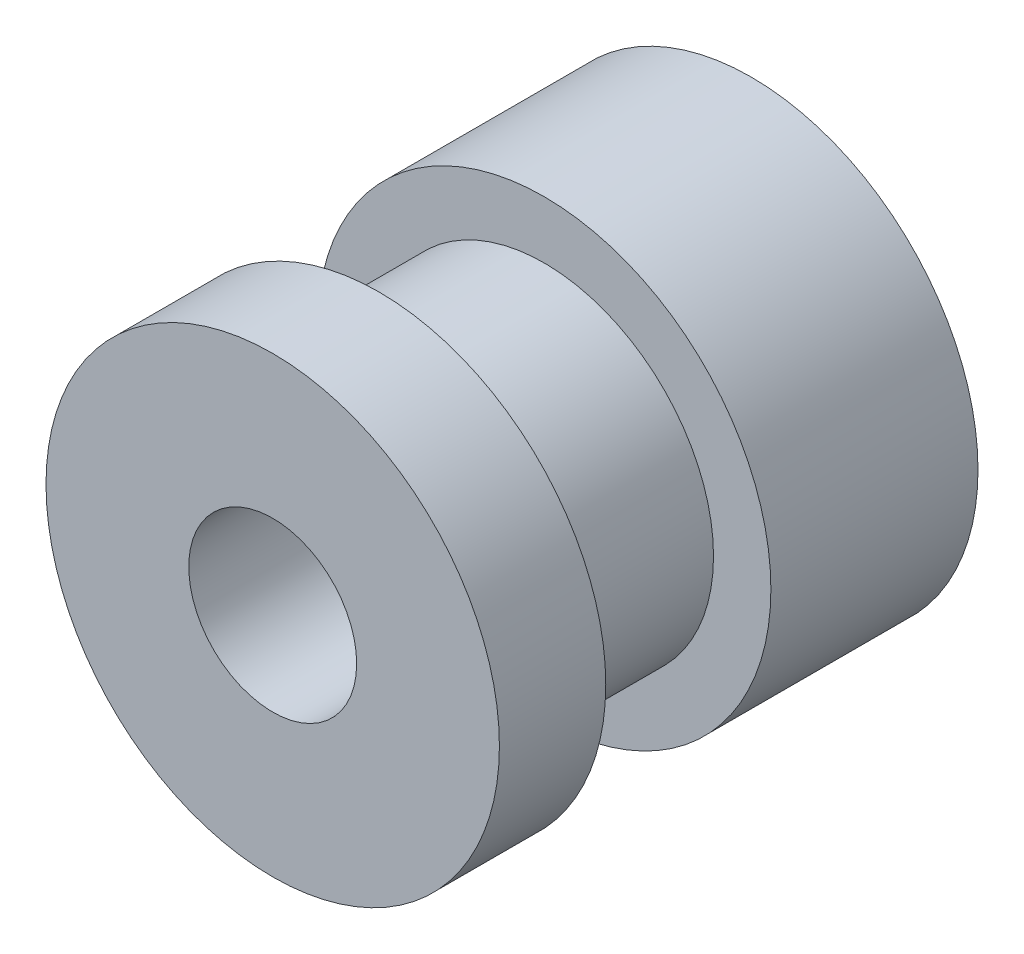
SolidWorks part; units mm, degrees
ref_plane "Front Plane" through (0, 0, 0) normal (0, 0, 1) x (1, 0, 0)
ref_plane "Top Plane" through (0, 0, 0) normal (0, 1, 0) x (1, 0, 0)
ref_plane "Right Plane" through (0, 0, 0) normal (1, 0, 0) x (0, 0, -1)
sketch "Sketch1" plane through (0, 0, 0) normal (0, 1, 0) x (1, 0, 0)
  line L0 (0, 0) -> (0, 15.8386) construction
  line L1 (-3, 0) -> (-8.1, 0)
  line L2 (-8.1, 0) -> (-8.1, 3.8)
  line L3 (-8.1, 3.8) -> (-6.05, 3.8)
  line L4 (-6.05, 3.8) -> (-6.05, 9.7)
  line L5 (-6.05, 9.7) -> (-8.1, 9.7)
  line L6 (-8.1, 9.7) -> (-8.1, 17.1)
  line L7 (-8.1, 17.1) -> (-3, 17.1)
  line L8 (-3, 17.1) -> (-3, 0)
  point P11 (-1.7247, 14.7353)
  point P12 (0, 0)
  dimension "D1" = 7.4
  dimension "D2" = 5.9
  dimension "D3" = 17.1
  dimension "D4" = 16.2
  dimension "D5" = 12.1
  dimension "D6" = 6
revolve "Revolve1" add sketch "Sketch1" angle 360 about L0
